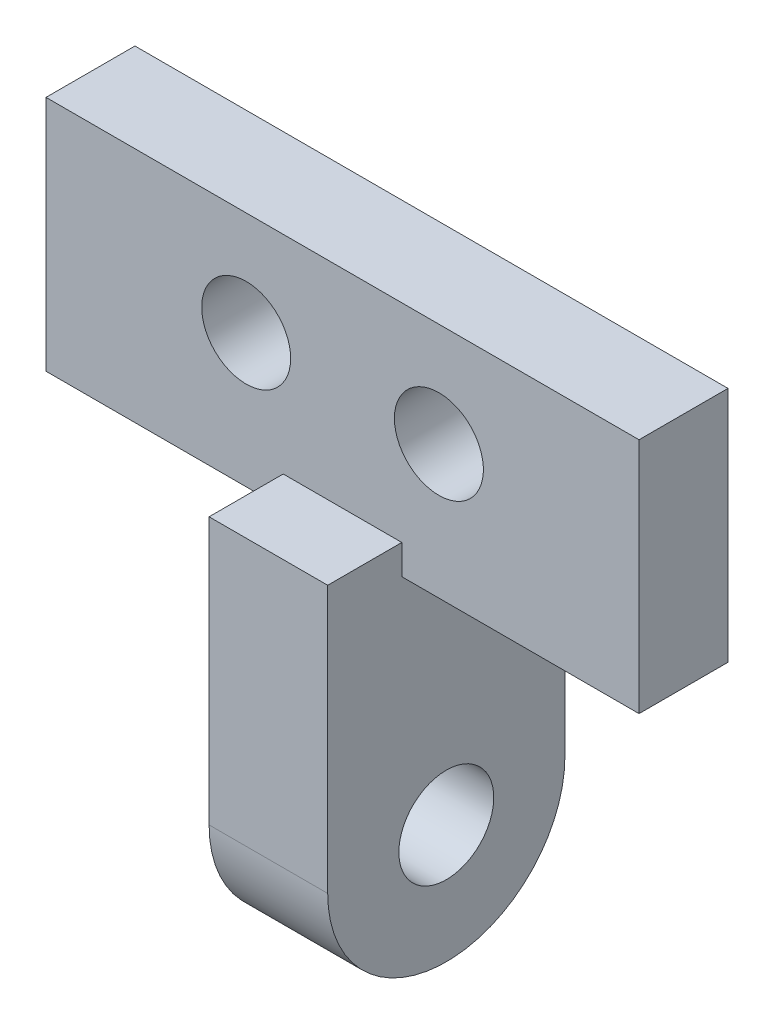
SolidWorks part; units mm, degrees
ref_plane "Front Plane" through (0, 0, 0) normal (0, 0, 1) x (1, 0, 0)
ref_plane "Top Plane" through (0, 0, 0) normal (0, 1, 0) x (1, 0, 0)
ref_plane "Right Plane" through (0, 0, 0) normal (1, 0, 0) x (0, 0, -1)
sketch "Sketch2" plane through (0, 0, 0) normal (0, 0, 1) x (1, 0, 0)
  line L0 (-10, 8) -> (10, 8)
  line L1 (-10, 8) -> (-10, 0)
  line L2 (10, 8) -> (10, 0)
  line L3 (-10, 0) -> (10, 0)
  line L4 (0, 0) -> (0, -11349.3187) construction
  circle A0 centre (-3.25, 4.5) radius 1.5
  circle A1 centre (3.25, 4.5) radius 1.5
  dimension "D4" = 3
  dimension "D1" = 10
  dimension "D2" = 8
  dimension "D3" = 10
  dimension "D5" = 3.5
  dimension "D6" = 6.5
extrude "Boss-Extrude3" add sketch "Sketch2" along normal blind 3
sketch "Sketch5" plane through (10, 0, 0) normal (1, 0, 0) x (0, 0, -1)
  line L1 (-5.5, 0) -> (-5.5, -8)
  line L2 (2.5, 0) -> (2.5, -8)
  line L3 (0, 0) -> (0, -50000) construction
  line L5 (-3, 0) -> (-3, 8) construction
  line L6 (0, 1) -> (0, 0)
  line L8 (-3, 1) -> (-3, 0)
  line L10 (-3, 0) -> (0, 0)
  line L15 (0, 1) -> (2.5, 1)
  line L16 (2.5, 1) -> (2.5, 0)
  line L17 (-3, 1) -> (-5.5, 1)
  line L18 (-5.5, 1) -> (-5.5, 0)
  arc A0 (-5.5, -8) -> (2.5, -8) centre (-1.5, -8) ccw
  circle A1 centre (-1.5, -8) radius 1.6
  point P3 (0, 0)
  dimension "D3" = 3.2
  dimension "D5" = 1
  dimension "D6" = 1
  dimension "D1" = 8
  dimension "D2" = 5.5
extrude "Boss-Extrude4" add sketch "Sketch5" along normal blind 4 from offset 12
